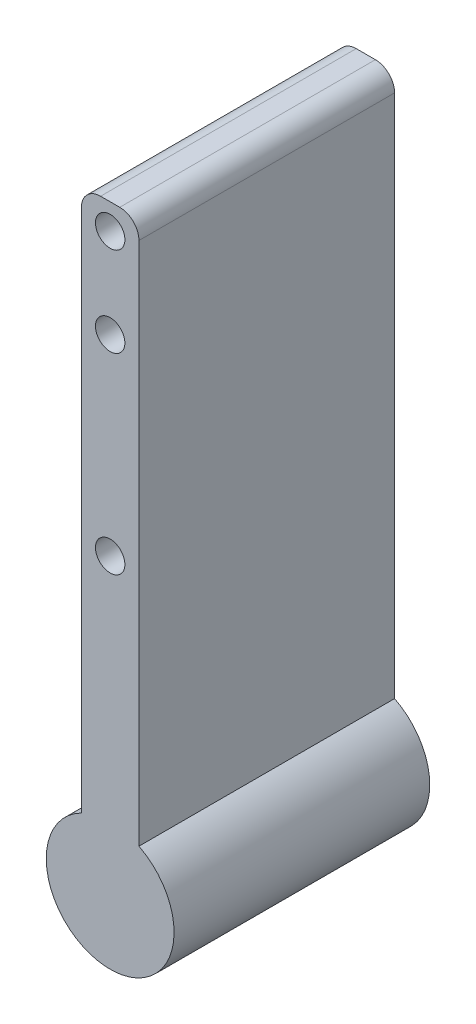
SolidWorks part; units mm, degrees
ref_plane "前视基准面" through (0, 0, 0) normal (0, 0, 1) x (1, 0, 0)
ref_plane "上视基准面" through (0, 0, 0) normal (0, 1, 0) x (1, 0, 0)
ref_plane "右视基准面" through (0, 0, 0) normal (1, 0, 0) x (0, 0, -1)
other "Configuration Table"
sketch "草图1" plane through (0, 0, 0) normal (0, 0, 1) x (1, 0, 0)
  line L0 (0, 0.0668) -> (0, -49999.9332) construction
  line L1 (-2.25, 23.5) -> (2.25, 23.5)
  line L2 (-2.25, 23.5) -> (-2.25, -23.5)
  line L3 (-2.25, -23.5) -> (2.25, -23.5)
  line L4 (2.25, 23.5) -> (2.25, -23.5)
  line L5 (-2.25, 23.5) -> (2.25, -23.5) construction
  line L6 (-2.25, -23.5) -> (2.25, 23.5) construction
  line L7 (0, -28.5) -> (50000, -28.5) construction
  circle A0 centre (0, -23.5) radius 5
  circle A1 centre (0, -0.5) radius 1.15
  circle A2 centre (0, 14.5) radius 1.15
  circle A3 centre (0, 21.5) radius 1.15
  point P0 (0, 0)
  dimension "D1" = 10
  dimension "D2" = 15
  dimension "D3" = 2.3
  dimension "D6" = 2
  dimension "D7" = 7
  dimension "D8" = 2.3
  dimension "D4" = 28
  dimension "D5" = 4.5
extrude "凸台-拉伸1" add sketch "草图1" along normal mid plane 20 contours A0 L4 L1 L2 A2 A1 | L2 A0 L4 L3 | L4 A0 L2 L3
fillet "圆角1" radius 1.5 2 edges at (2.25, 23.5, 0) (-2.25, 23.5, 0)
